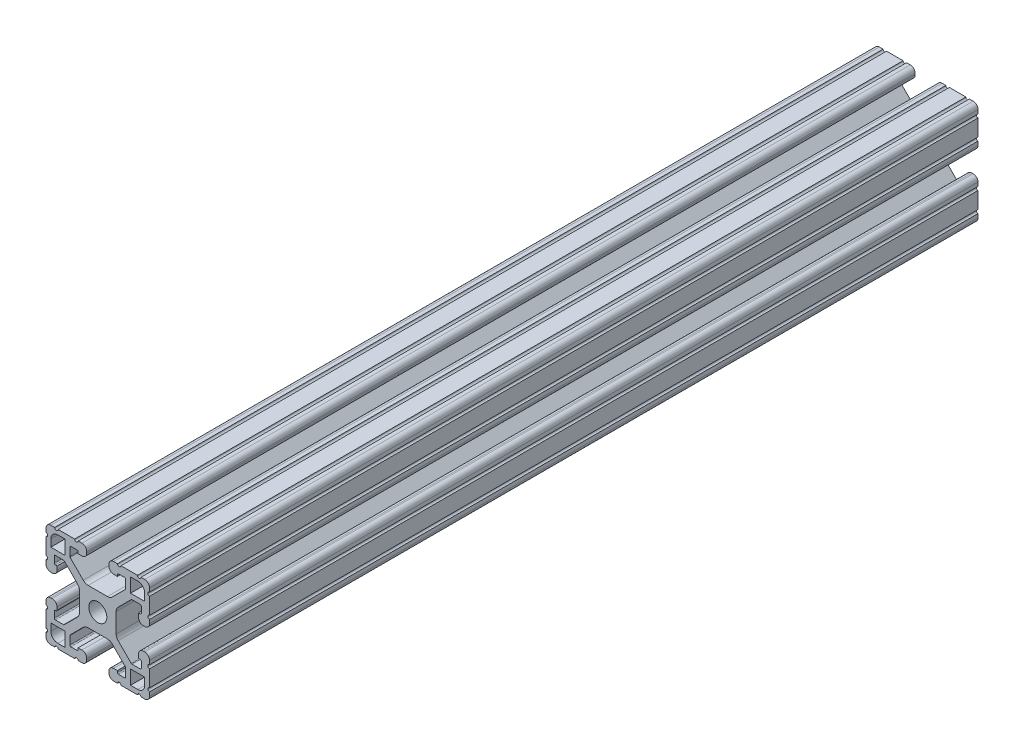
SolidWorks part; units mm, degrees
ref_plane "Front Plane" through (0, 0, 0) normal (0, 0, 1) x (1, 0, 0)
ref_plane "Top Plane" through (0, 0, 0) normal (0, 1, 0) x (1, 0, 0)
ref_plane "Right Plane" through (0, 0, 0) normal (1, 0, 0) x (0, 0, -1)
sketch "Sketch1" plane through (0, 0, 0) normal (0, 0, 1) x (1, 0, 0)
  line L0 (0, -19.05) -> (0, 19.05) construction
  line L1 (19.05, 0) -> (-19.05, 0) construction
  line L2 (4.064, 19.05) -> (-4.064, 19.05) construction
  line L3 (0, -6.7564) -> (0, 6.7564) construction
  line L4 (-4.064, 19.05) -> (-4.064, 14.986) construction
  line L5 (19.05, -10.287) -> (19.05, 10.287) construction
  line L6 (0, -3.3274) -> (0, 3.3274) construction
  line L7 (0, 0) -> (-19.05, 19.05) construction
  line L8 (-8.4474, 10.6026) -> (-10.6026, 8.4474) construction
  point P4 (0, 0)
  point P8 (0, 0)
  point P11 (0, 19.05)
  point P14 (0, 0)
  point P18 (19.05, 0)
  point P21 (0, 0)
  point P24 (-9.525, 9.525)
  point P26 (-9.525, 9.525)
  dimension "T-Slot Width" = 8.128
  dimension "Thickness" = 4.064
  dimension "Opening Width" = 20.574
  dimension "Slot Depth" = 12.2936
  dimension "Center Hole Diameter" = 6.6548
  dimension "Rail Height" = 38.1
  dimension "Rail Width" = 38.1
  dimension "D1" = 45
  dimension "Wall" = 3.048
sketch "Sketch2" plane through (0, 0, 0) normal (1, 0, 0) x (0, 0, -1)
  line L0 (-152.4, 0) -> (152.4, 0) construction
  line L1 (-76.2, -19.05) -> (-76.2, 19.05) construction
  line L2 (76.2, -19.05) -> (76.2, 19.05) construction
  line L3 (0, -19.05) -> (0, 19.05) construction
  point P4 (0, 0)
  point P7 (-76.2, 0)
  point P10 (76.2, 0)
  dimension "Length" = 304.8
  dimension "D1" = 76.2
  dimension "D2" = 76.2
sketch "Sketch3" plane through (0, 0, 0) normal (0, 0, 1) x (1, 0, 0)
  line L1 (19.05, -19.05) -> (-19.05, -19.05)
  line L2 (19.05, -19.05) -> (19.05, 19.05)
  line L3 (19.05, 19.05) -> (-19.05, 19.05)
  line L4 (-19.05, -19.05) -> (-19.05, 19.05)
  line L5 (19.05, -19.05) -> (-19.05, 19.05) construction
  line L6 (19.05, 19.05) -> (-19.05, -19.05) construction
  point P0 (0, 0)
extrude "Boss-Extrude1" add sketch "Sketch3" along normal up to vertex (152.4 mm away) and the other way up to vertex (152.4 mm away) up to point (0, 0, 152.4) other way up to point (0, 0, -152.4)
sketch "Sketch4" plane through (0, 0, 152.4) normal (0, 0, 1) x (1, 0, 0)
  line L4 (4.064, 14.986) -> (4.064, 19.05)
  line L5 (7.239, 14.986) -> (4.064, 14.986)
  line L6 (19.05, 0) -> (-19.05, 0) construction
  line L7 (4.6011, 6.7564) -> (-4.6011, 6.7564)
  line L8 (-4.6011, 6.7564) -> (-10.287, 12.4423)
  line L37 (-19.05, 19.05) -> (-19.05, -19.05) construction
  line L38 (-19.05, -19.05) -> (19.05, -19.05) construction
  line L39 (-10.287, 12.4423) -> (-10.287, 16.002)
  line L40 (-10.287, 16.002) -> (-7.239, 16.002)
  line L41 (-7.239, 16.002) -> (-7.239, 14.986)
  line L42 (-7.239, 14.986) -> (-4.064, 14.986)
  line L43 (-4.064, 14.986) -> (-4.064, 19.05)
  line L44 (-4.064, 19.05) -> (4.064, 19.05)
  line L45 (0, 19.05) -> (0, 0) construction
  line L46 (-19.05, 19.05) -> (0, 0) construction
  line L47 (7.239, 16.002) -> (7.239, 14.986)
  line L48 (10.287, 16.002) -> (7.239, 16.002)
  line L49 (10.287, 12.4423) -> (10.287, 16.002)
  line L50 (4.6011, 6.7564) -> (10.287, 12.4423)
  line L51 (-19.05, 0) -> (19.05, 0) construction
  line L52 (4.6011, -6.7564) -> (10.287, -12.4423)
  line L53 (10.287, -12.4423) -> (10.287, -16.002)
  line L54 (10.287, -16.002) -> (7.239, -16.002)
  line L55 (7.239, -16.002) -> (7.239, -14.986)
  line L56 (-4.064, -19.05) -> (4.064, -19.05)
  line L57 (-4.064, -14.986) -> (-4.064, -19.05)
  line L58 (-7.239, -14.986) -> (-4.064, -14.986)
  line L59 (-7.239, -16.002) -> (-7.239, -14.986)
  line L60 (-10.287, -16.002) -> (-7.239, -16.002)
  line L61 (-10.287, -12.4423) -> (-10.287, -16.002)
  line L62 (-4.6011, -6.7564) -> (-10.287, -12.4423)
  line L63 (4.6011, -6.7564) -> (-4.6011, -6.7564)
  line L64 (7.239, -14.986) -> (4.064, -14.986)
  line L65 (4.064, -14.986) -> (4.064, -19.05)
  line L66 (-6.7564, -4.6011) -> (-12.4423, -10.287)
  line L67 (-12.4423, -10.287) -> (-16.002, -10.287)
  line L68 (-16.002, -10.287) -> (-16.002, -7.239)
  line L69 (-16.002, -7.239) -> (-14.986, -7.239)
  line L70 (-19.05, 4.064) -> (-19.05, -4.064)
  line L71 (-14.986, 4.064) -> (-19.05, 4.064)
  line L72 (-14.986, 7.239) -> (-14.986, 4.064)
  line L73 (-16.002, 7.239) -> (-14.986, 7.239)
  line L74 (-16.002, 10.287) -> (-16.002, 7.239)
  line L75 (-12.4423, 10.287) -> (-16.002, 10.287)
  line L76 (-6.7564, 4.6011) -> (-12.4423, 10.287)
  line L77 (-6.7564, -4.6011) -> (-6.7564, 4.6011)
  line L78 (-14.986, -7.239) -> (-14.986, -4.064)
  line L79 (-14.986, -4.064) -> (-19.05, -4.064)
  line L80 (14.986, -4.064) -> (19.05, -4.064)
  line L81 (14.986, -7.239) -> (14.986, -4.064)
  line L82 (6.7564, -4.6011) -> (6.7564, 4.6011)
  line L83 (6.7564, 4.6011) -> (12.4423, 10.287)
  line L84 (12.4423, 10.287) -> (16.002, 10.287)
  line L85 (16.002, 10.287) -> (16.002, 7.239)
  line L86 (16.002, 7.239) -> (14.986, 7.239)
  line L87 (14.986, 7.239) -> (14.986, 4.064)
  line L88 (14.986, 4.064) -> (19.05, 4.064)
  line L89 (19.05, 4.064) -> (19.05, -4.064)
  line L90 (16.002, -7.239) -> (14.986, -7.239)
  line L91 (16.002, -10.287) -> (16.002, -7.239)
  line L92 (12.4423, -10.287) -> (16.002, -10.287)
  line L93 (6.7564, -4.6011) -> (12.4423, -10.287)
  line L94 (19.05, -19.05) -> (19.05, 19.05) construction
  line L95 (12.065, 17.272) -> (17.272, 17.272)
  line L96 (12.065, 17.272) -> (12.065, 12.065)
  line L97 (12.065, 12.065) -> (17.272, 12.065)
  line L98 (17.272, 17.272) -> (17.272, 12.065)
  line L99 (19.05, 19.05) -> (-19.05, 19.05) construction
  line L100 (17.272, -17.272) -> (17.272, -12.065)
  line L101 (12.065, -17.272) -> (17.272, -17.272)
  line L102 (12.065, -17.272) -> (12.065, -12.065)
  line L103 (12.065, -12.065) -> (17.272, -12.065)
  line L104 (-17.272, 17.272) -> (-17.272, 12.065)
  line L105 (-12.065, 12.065) -> (-17.272, 12.065)
  line L106 (-12.065, 17.272) -> (-12.065, 12.065)
  line L107 (-12.065, 17.272) -> (-17.272, 17.272)
  line L108 (-12.065, -12.065) -> (-17.272, -12.065)
  line L109 (-12.065, -17.272) -> (-12.065, -12.065)
  line L110 (-12.065, -17.272) -> (-17.272, -17.272)
  line L111 (-17.272, -17.272) -> (-17.272, -12.065)
  circle A5 centre (0, 0) radius 3.3274
  point P21 (0, 6.7564)
  point P23 (0, -6.7564)
  point P38 (-6.7564, 0)
  point P53 (6.7564, 0)
  dimension "D1" = 20.574
  dimension "D3" = 3.048
  dimension "D4" = 3.048
  dimension "D5" = 1.778
  dimension "D6" = 1.778
  dimension "D7" = 1.778
extrude "Cut-Extrude1" cut sketch "Sketch4" against normal through all
sketch "Sketch5" plane through (0, 0, 152.4) normal (0, 0, 1) x (1, 0, 0)
  line L4 (-4.064, 19.05) -> (-19.05, 19.05) construction
  line L26 (-19.05, 19.05) -> (-19.05, 4.064) construction
  line L27 (-15.875, 19.05) -> (-14.605, 19.05)
  line L28 (-8.509, 19.05) -> (-7.239, 19.05)
  line L29 (-19.05, 15.875) -> (-19.05, 14.605)
  line L30 (-19.05, 8.509) -> (-19.05, 7.239)
  line L31 (8.509, 19.05) -> (7.239, 19.05)
  line L32 (15.875, 19.05) -> (14.605, 19.05)
  line L33 (19.05, 15.875) -> (19.05, 14.605)
  line L34 (19.05, 8.509) -> (19.05, 7.239)
  line L35 (19.05, -8.509) -> (19.05, -7.239)
  line L36 (19.05, -15.875) -> (19.05, -14.605)
  line L37 (15.875, -19.05) -> (14.605, -19.05)
  line L38 (8.509, -19.05) -> (7.239, -19.05)
  line L39 (-8.509, -19.05) -> (-7.239, -19.05)
  line L40 (-15.875, -19.05) -> (-14.605, -19.05)
  line L41 (-19.05, -15.875) -> (-19.05, -14.605)
  line L42 (-19.05, -8.509) -> (-19.05, -7.239)
  line L43 (19.05, 19.05) -> (4.064, 19.05) construction
  line L44 (19.05, 4.064) -> (19.05, 19.05) construction
  line L48 (-14.986, 4.064) -> (-19.05, 4.064) construction
  line L49 (-4.064, 14.986) -> (-4.064, 19.05) construction
  arc A8 (-15.875, 19.05) -> (-14.605, 19.05) centre (-15.24, 19.05) ccw
  arc A9 (-8.509, 19.05) -> (-7.239, 19.05) centre (-7.874, 19.05) ccw
  arc A10 (-19.05, 14.605) -> (-19.05, 15.875) centre (-19.05, 15.24) ccw
  arc A11 (-19.05, 7.239) -> (-19.05, 8.509) centre (-19.05, 7.874) ccw
  arc A12 (7.239, 19.05) -> (8.509, 19.05) centre (7.874, 19.05) ccw
  arc A13 (14.605, 19.05) -> (15.875, 19.05) centre (15.24, 19.05) ccw
  arc A14 (19.05, 15.875) -> (19.05, 14.605) centre (19.05, 15.24) ccw
  arc A15 (19.05, 8.509) -> (19.05, 7.239) centre (19.05, 7.874) ccw
  arc A16 (19.05, -7.239) -> (19.05, -8.509) centre (19.05, -7.874) ccw
  arc A17 (19.05, -14.605) -> (19.05, -15.875) centre (19.05, -15.24) ccw
  arc A18 (15.875, -19.05) -> (14.605, -19.05) centre (15.24, -19.05) ccw
  arc A19 (8.509, -19.05) -> (7.239, -19.05) centre (7.874, -19.05) ccw
  arc A20 (-7.239, -19.05) -> (-8.509, -19.05) centre (-7.874, -19.05) ccw
  arc A21 (-14.605, -19.05) -> (-15.875, -19.05) centre (-15.24, -19.05) ccw
  arc A22 (-19.05, -15.875) -> (-19.05, -14.605) centre (-19.05, -15.24) ccw
  arc A23 (-19.05, -8.509) -> (-19.05, -7.239) centre (-19.05, -7.874) ccw
  dimension "D2" = 0.635
  dimension "D4" = 3.81
  dimension "D5" = 3.81
  dimension "D1" = 3.81
  dimension "D3" = 3.81
  dimension "D7" = 4
extrude "Cut-Extrude2" cut sketch "Sketch5" against normal through all
fillet "Fillet1" radius 2.54 12 edges at (-6.7564, 4.6011, 0) (-6.7564, -4.6011, 0) (4.6011, -6.7564, 0) (-4.6011, -6.7564, 0) (6.7564, -4.6011, 0) (6.7564, 4.6011, 0) (4.6011, 6.7564, 0) (-4.6011, 6.7564, 0) (-17.272, 17.272, 0) (17.272, 17.272, 0) (17.272, -17.272, 0) (-17.272, -17.272, 0)
fillet "Fillet2" radius 1.778 20 edges at (19.05, -19.05, 0) (19.05, 19.05, 0) (-19.05, -19.05, 0) (-19.05, 19.05, 0) (-14.986, 4.064, 0) (-19.05, 4.064, 0) (-19.05, -4.064, 0) (-14.986, -4.064, 0) (-4.064, -19.05, 0) (-4.064, -14.986, 0) (4.064, -14.986, 0) (4.064, -19.05, 0) (19.05, -4.064, 0) (14.986, -4.064, 0) (19.05, 4.064, 0) (14.986, 4.064, 0) (4.064, 14.986, 0) (4.064, 19.05, 0) (-4.064, 19.05, 0) (-4.064, 14.986, 0)
fillet "Fillet3" radius 0.3969 24 edges at (-14.986, -7.239, 0) (-16.002, -10.287, 0) (-12.4423, -10.287, 0) (-12.4423, 10.287, 0) (-16.002, 7.239, 0) (-16.002, 10.287, 0) (-10.287, 12.4423, 0) (-7.239, 16.002, 0) (-10.287, 16.002, 0) (10.287, 16.002, 0) (7.239, 16.002, 0) (10.287, 12.4423, 0) (16.002, 10.287, 0) (12.4423, 10.287, 0) (16.002, 7.239, 0) (16.002, -7.239, 0) (16.002, -10.287, 0) (12.4423, -10.287, 0) (10.287, -12.4423, 0) (10.287, -16.002, 0) (7.239, -16.002, 0) (-7.239, -16.002, 0) (-10.287, -12.4423, 0) (-10.287, -16.002, 0)
equation "\"D4@Sketch5\"=\"D3@Sketch5\""
equation "\"D5@Sketch5\"=\"D4@Sketch5\""
equation "\"D1@Sketch4\"=\"Opening Width@Sketch1\""
equation "\"D2@Sketch2\"=\"D1@Sketch2\""
